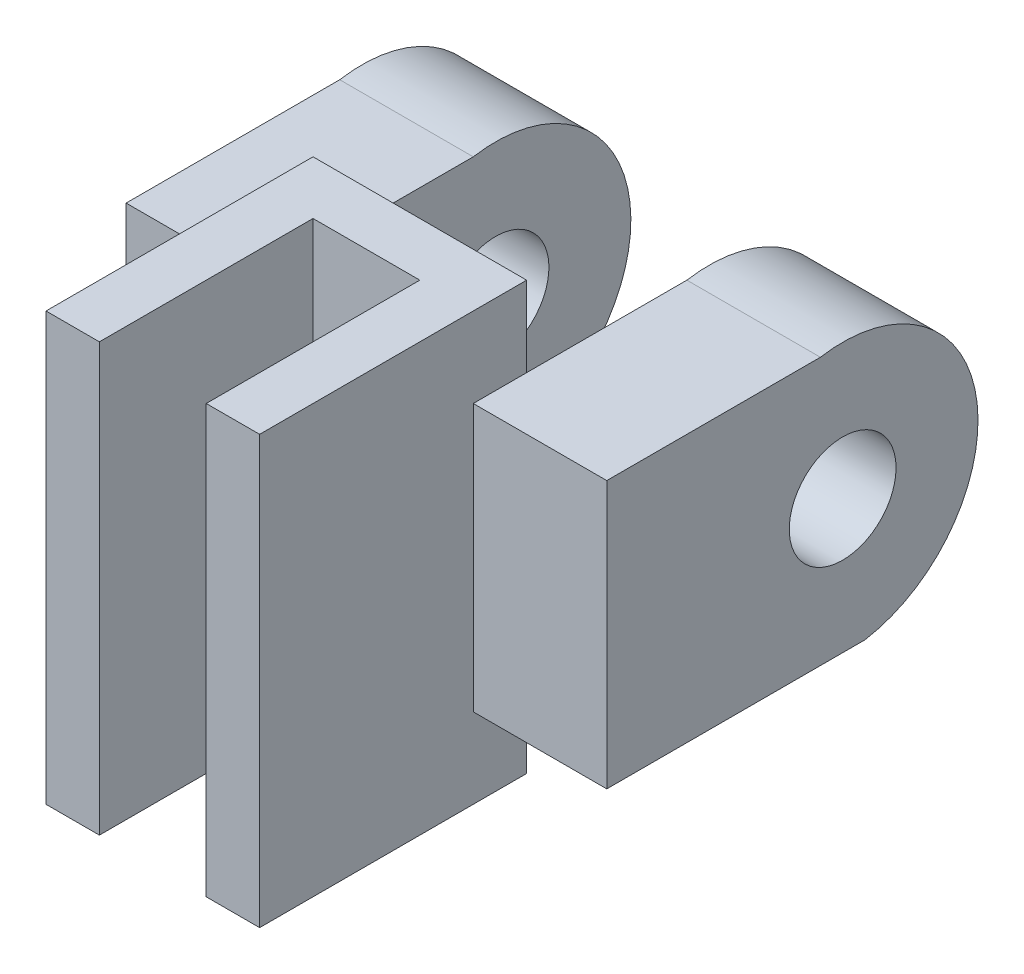
SolidWorks part; units mm, degrees
ref_plane "Front Plane" through (0, 0, 0) normal (0, 0, 1) x (1, 0, 0)
ref_plane "Top Plane" through (0, 0, 0) normal (0, 1, 0) x (1, 0, 0)
ref_plane "Right Plane" through (0, 0, 0) normal (1, 0, 0) x (0, 0, -1)
sketch "Sketch1" plane through (0, 0, 0) normal (0, 0, 1) x (1, 0, 0)
  line L1 (2, 2.5) -> (-2, 2.5)
  line L2 (2, 2.5) -> (2, -2.5)
  line L3 (2, -2.5) -> (-2, -2.5)
  line L4 (-2, 2.5) -> (-2, -2.5)
  line L5 (2, 2.5) -> (-2, -2.5) construction
  line L6 (2, -2.5) -> (-2, 2.5) construction
  point P0 (0, 0)
  dimension "D1" = 5
  dimension "D2" = 4
extrude "Boss-Extrude1" add sketch "Sketch1" along normal blind 3
sketch "Sketch2" plane through (0, 0, 3) normal (0, 0, 1) x (1, 0, 0)
  line L0 (-2, -2.5) -> (2, -2.5) construction
  line L1 (1, 2.5) -> (-1, 2.5)
  line L2 (1, 2.5) -> (1, -2.5)
  line L3 (1, -2.5) -> (-1, -2.5)
  line L4 (-1, 2.5) -> (-1, -2.5)
  line L5 (1, 2.5) -> (-1, -2.5) construction
  line L6 (1, -2.5) -> (-1, 2.5) construction
  point P0 (0, 0)
  dimension "D1" = 2
extrude "Cut-Extrude1" cut sketch "Sketch2" against normal blind 2
sketch "Sketch3" plane through (2, 0, 0) normal (1, 0, 0) x (0, 0, -1)
  line L1 (0, 2.5) -> (3, 2.5)
  line L2 (0, 2.5) -> (0, -2.5)
  line L3 (0, -2.5) -> (3.8334, -2.5)
  line L5 (0, 2.5) -> (3.8334, -2.5) construction
  line L6 (0, -2.5) -> (3, 2.5) construction
  arc A0 (3, 2.5) -> (3.8334, -2.5) centre (3.4167, 0) cw
  circle A1 centre (3.4167, 0) radius 1
  point P4 (1.6829, 0.3049)
  point P9 (0, 0)
  dimension "D1" = 2
  dimension "D2" = 3
extrude "Boss-Extrude2" add sketch "Sketch3" along normal blind 2.5 and the other way blind 1
mirror "Mirror1" about plane through (0, 0, 0) normal (1, 0, 0) of "Boss-Extrude2"
sketch "Sketch4" plane through (0, -2.5, 0) normal (0, -1, 0) x (1, 0, 0)
  line L0 (-4.5, -5.9512) -> (-1, -5.9512) construction
  line L1 (2, 0) -> (-2, 0)
  line L2 (2, 0) -> (2, -5.9512)
  line L3 (2, -5.9512) -> (-2, -5.9512)
  line L4 (-2, 0) -> (-2, -5.9512)
  line L5 (2, 0) -> (-2, -5.9512) construction
  line L6 (2, -5.9512) -> (-2, 0) construction
  point P4 (0, -2.9756)
extrude "Cut-Extrude2" cut sketch "Sketch4" against normal through all
sketch "Sketch5" plane through (0, -2.5, 0) normal (0, -1, 0) x (1, 0, 0)
  line L0 (-1, 1) -> (1, 1) construction
  line L1 (4.5, 0) -> (-4.5, 0)
  line L2 (4.5, 0) -> (4.5, 1)
  line L3 (4.5, 1) -> (-4.5, 1)
  line L4 (-4.5, 0) -> (-4.5, 1)
  line L5 (4.5, 0) -> (-4.5, 1) construction
  line L6 (4.5, 1) -> (-4.5, 0) construction
  point P4 (0, 0.5)
extrude "Boss-Extrude3" add sketch "Sketch5" against normal blind 5
sketch "Sketch6" plane through (0, 2.5, 0) normal (0, 1, 0) x (1, 0, 0)
  line L0 (-1, -3) -> (-1, -1)
  line L1 (2, 0) -> (-2, 0)
  line L2 (2, 0) -> (2, -3)
  line L3 (2, -3) -> (1, -3)
  line L4 (-2, 0) -> (-2, -3)
  line L5 (2, 0) -> (-2, -3) construction
  line L6 (2, -3) -> (-2, 0) construction
  line L7 (-1, -1) -> (1, -1)
  line L8 (1, -1) -> (1, -3)
  line L9 (-1, -3) -> (-2, -3)
  point P4 (0, -1.5)
extrude "Boss-Extrude4" add sketch "Sketch6" along normal blind 1.5 and the other way blind 6.5
sketch "Sketch7" plane through (0, 0, 3) normal (0, 0, 1) x (1, 0, 0)
  line L0 (1, 4) -> (2, 4) construction
  line L1 (1, -4) -> (1, 4) construction
  line L2 (2, -4) -> (2, 4) construction
  line L3 (1, -4) -> (2, -4) construction
  line L4 (-2, -4) -> (-1, -4) construction
  line L5 (-2, 4) -> (-2, -4) construction
  line L6 (-1, 4) -> (-1, -4) construction
  line L7 (-2, 4) -> (-1, 4) construction
  line L8 (1, 4) -> (2, 4)
  line L9 (1, -4) -> (1, 4)
  line L10 (2, -4) -> (2, 4)
  line L11 (1, -4) -> (2, -4)
  line L12 (-2, -4) -> (-1, -4)
  line L13 (-2, 4) -> (-2, -4)
  line L14 (-1, 4) -> (-1, -4)
  line L15 (-2, 4) -> (-1, 4)
extrude "Boss-Extrude5" add sketch "Sketch7" along normal blind 2
